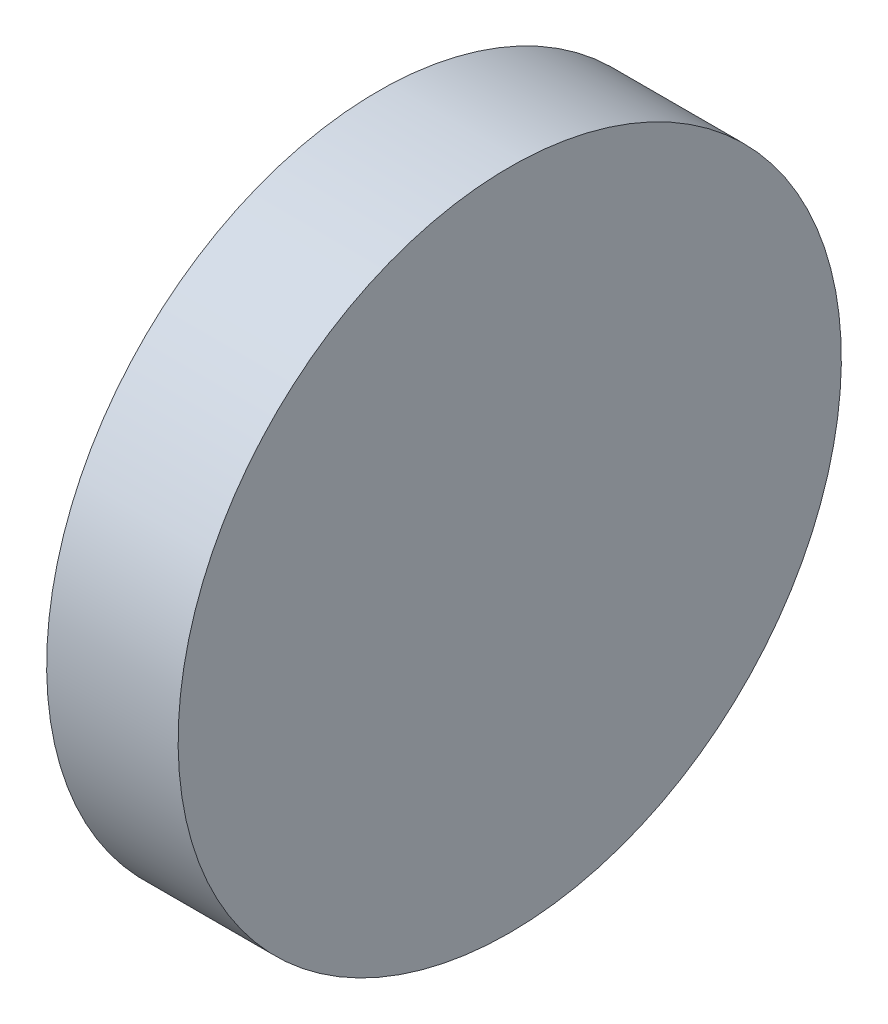
SolidWorks part; units mm, degrees
ref_plane "Front Plane" through (0, 0, 0) normal (0, 0, 1) x (1, 0, 0)
ref_plane "Top Plane" through (0, 0, 0) normal (0, 1, 0) x (1, 0, 0)
ref_plane "Right Plane" through (0, 0, 0) normal (1, 0, 0) x (0, 0, -1)
sketch "Sketch1" plane through (0, 0, 0) normal (0, 0, 1) x (1, 0, 0)
  line L1 (-0.785, 3.96) -> (0.785, 3.96)
  line L2 (-0.785, 3.96) -> (-0.785, 0)
  line L3 (-0.785, 0) -> (0.785, 0)
  line L4 (0.785, 3.96) -> (0.785, 0)
  dimension "D1" = 3.96
  dimension "D2" = 1.57
revolve "Revolve1" add sketch "Sketch1" angle 360 about L3
